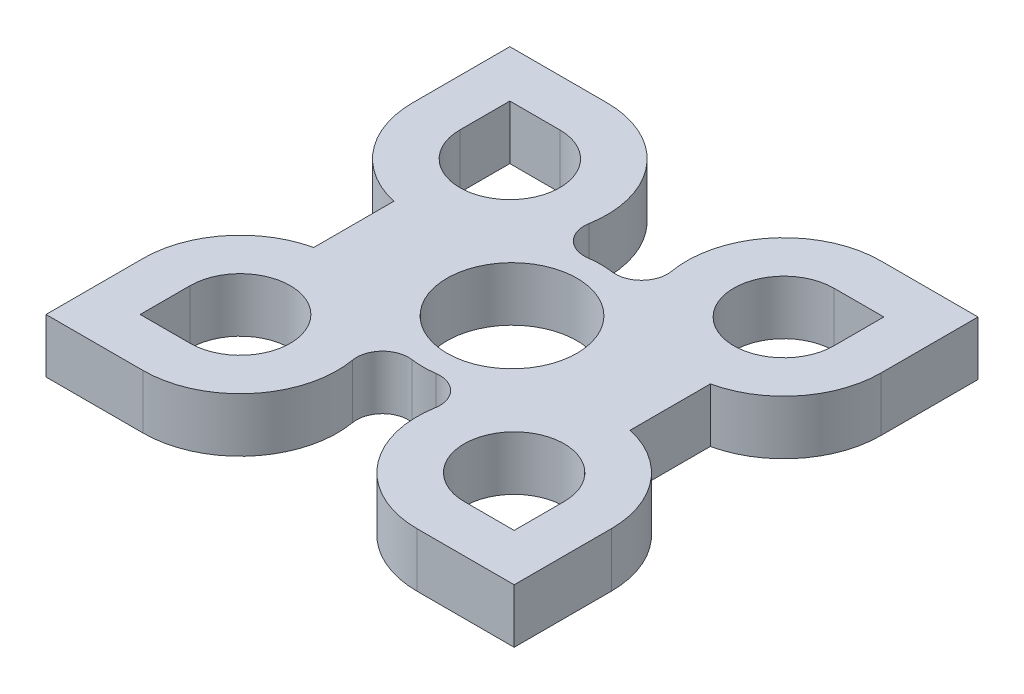
SolidWorks part; units mm, degrees
ref_plane "Front Plane" through (0, 0, 0) normal (0, 0, 1) x (1, 0, 0)
ref_plane "Top Plane" through (0, 0, 0) normal (0, 1, 0) x (1, 0, 0)
ref_plane "Right Plane" through (0, 0, 0) normal (1, 0, 0) x (0, 0, -1)
sketch "Sketch1" plane through (0, 0, 0) normal (0, 1, 0) x (1, 0, 0)
  line L0 (0, -50000) -> (0, 50000) construction
  line L5 (73, 18.485) -> (73, -18.485)
  line L6 (-108, 107) -> (-63.2, 107)
  line L7 (50000, 0) -> (-50000, 0) construction
  line L8 (-108, 107) -> (-108, 62.2)
  line L9 (-108, -107) -> (-63.2, -107)
  line L10 (108, 107) -> (108, 62.2)
  line L11 (-108, 107) -> (108, -107) construction
  line L12 (-108, -107) -> (0, 0) construction
  line L13 (86.2749, 85.2749) -> (86.2749, 62.2)
  line L14 (63.2, 85.2749) -> (86.2749, 85.2749)
  line L15 (86.2749, -85.2749) -> (86.2749, -62.2)
  line L16 (63.2, -85.2749) -> (86.2749, -85.2749)
  line L17 (-86.2749, -85.2749) -> (-86.2749, -62.2)
  line L18 (-63.2, -85.2749) -> (-86.2749, -85.2749)
  line L19 (-73, 18.485) -> (-73, -18.485)
  line L20 (-63.2, 85.2749) -> (-86.2749, 85.2749)
  line L21 (-86.2749, 85.2749) -> (-86.2749, 62.2)
  line L22 (-108, -62.2) -> (-108, -107)
  line L23 (63.2, 107) -> (108, 107)
  line L24 (108, -62.2) -> (108, -107)
  line L25 (63.2, -107) -> (108, -107)
  arc A0 (63.2, 107) -> (19.0576, 54.5525) centre (63.2, 62.2) ccw
  arc A1 (63.2, 85.2749) -> (86.2749, 62.2) centre (63.2, 62.2) ccw
  circle A2 centre (0, 0) radius 30
  arc A3 (-5.5959, -40.6163) -> (5.5959, -40.6163) centre (0, 0) ccw
  arc A4 (5.5959, 40.6163) -> (19.0576, 54.5525) centre (7.2337, 52.504) ccw
  arc A5 (73, 18.485) -> (108, 62.2) centre (63.2, 62.2) ccw
  arc A6 (73, -18.485) -> (108, -62.2) centre (63.2, -62.2) cw
  arc A7 (63.2, -85.2749) -> (86.2749, -62.2) centre (63.2, -62.2) cw
  arc A8 (63.2, -107) -> (19.0576, -54.5525) centre (63.2, -62.2) cw
  arc A9 (5.5959, -40.6163) -> (19.0576, -54.5525) centre (7.2337, -52.504) cw
  arc A10 (-63.2, -85.2749) -> (-86.2749, -62.2) centre (-63.2, -62.2) ccw
  arc A11 (-63.2, -107) -> (-19.0576, -54.5525) centre (-63.2, -62.2) ccw
  arc A12 (-5.5959, -40.6163) -> (-19.0576, -54.5525) centre (-7.2337, -52.504) ccw
  arc A13 (-5.5959, 40.6163) -> (-19.0576, 54.5525) centre (-7.2337, 52.504) cw
  arc A14 (-73, -18.485) -> (-108, -62.2) centre (-63.2, -62.2) ccw
  arc A15 (-63.2, 85.2749) -> (-86.2749, 62.2) centre (-63.2, 62.2) cw
  arc A16 (-73, 18.485) -> (-108, 62.2) centre (-63.2, 62.2) cw
  arc A17 (-63.2, 107) -> (-19.0576, 54.5525) centre (-63.2, 62.2) cw
  arc A19 (5.5959, 40.6163) -> (-5.5959, 40.6163) centre (0, 0) ccw
  point P0 (0, 0)
  point P15 (0, 0)
  point P25 (73, 0)
  dimension "D3" = 23.0749
  dimension "D4" = 41
  dimension "D6" = 5.5959
  dimension "D7" = 19.0576
  dimension "D8" = 73
  dimension "D5" = 12
  dimension "D2" = 44.8
  dimension "D1" = 60
extrude "Boss-Extrude1" add sketch "Sketch1" along normal blind 25
